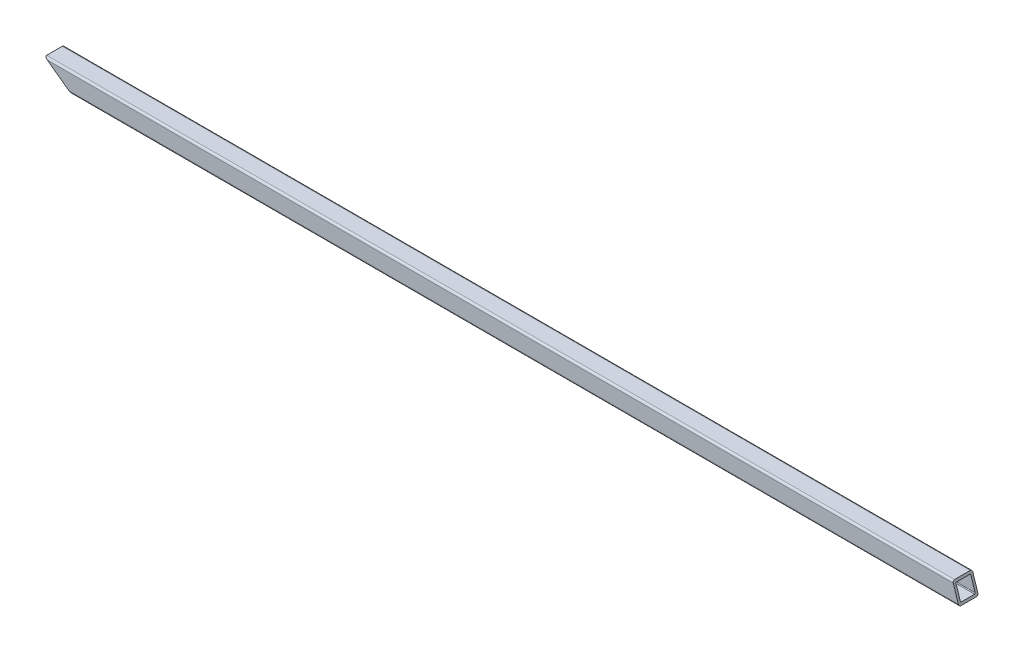
SolidWorks part; units mm, degrees
ref_plane "Front Plane" through (0, 0, 0) normal (0, 0, 1) x (1, 0, 0)
ref_plane "Top Plane" through (0, 0, 0) normal (0, 1, 0) x (1, 0, 0)
ref_plane "Right Plane" through (0, 0, 0) normal (1, 0, 0) x (0, 0, -1)
sketch "Sketch3" plane through (0, 0, 0) normal (1, 0, 0) x (0, 0, -1)
  line L1 (-12.7, 12.7) -> (12.7, 12.7)
  line L2 (-12.7, 12.7) -> (-12.7, -12.7)
  line L3 (-12.7, -12.7) -> (12.7, -12.7)
  line L4 (12.7, 12.7) -> (12.7, -12.7)
  line L5 (-12.7, 12.7) -> (12.7, -12.7) construction
  line L6 (-12.7, -12.7) -> (12.7, 12.7) construction
  line L7 (-9.652, -9.652) -> (9.652, -9.652)
  line L8 (-9.652, -9.652) -> (-9.652, 9.652)
  line L9 (-9.652, 9.652) -> (9.652, 9.652)
  line L10 (9.652, -9.652) -> (9.652, 9.652)
  line L11 (-9.652, -9.652) -> (9.652, 9.652) construction
  line L12 (-9.652, 9.652) -> (9.652, -9.652) construction
  point P0 (0, 0)
  point P6 (0, 0)
  dimension "D1" = 25.4
  dimension "D2" = 19.304
  dimension "D3" = 19.304
  dimension "D4" = 25.4
extrude "Boss-Extrude1" add sketch "Sketch3" against normal blind 1190.03
fillet "Fillet1" radius 2.5 4 edges at (-595.015, -12.7, -12.7) (-595.015, -12.7, 12.7) (-595.015, 12.7, -12.7) (-595.015, 12.7, 12.7)
fillet "Fillet2" radius 1 4 edges at (-595.015, -9.652, -9.652) (-595.015, 9.652, -9.652) (-595.015, 9.652, 9.652) (-595.015, -9.652, 9.652)
sketch "Sketch5" plane through (0, 0, -12.7) normal (0, 0, -1) x (-1, 0, 0)
  line L0 (1190.03, 12.7) -> (1155.0699, -12.7)
  line L1 (0, -12.7) -> (1190.03, -12.7) construction
  line L2 (1155.0699, -12.7) -> (1190.03, -12.7)
  line L3 (1190.03, -12.7) -> (1190.03, 12.7)
  line L4 (0, 12.7) -> (8.253, 12.7)
  line L5 (1190.03, 12.7) -> (0, 12.7) construction
  line L6 (8.253, 12.7) -> (0, -12.7)
  line L7 (0, -12.7) -> (0, 12.7)
  dimension "D1" = 36
  dimension "D2" = 18
extrude "Cut-Extrude1" cut sketch "Sketch5" against normal through all
